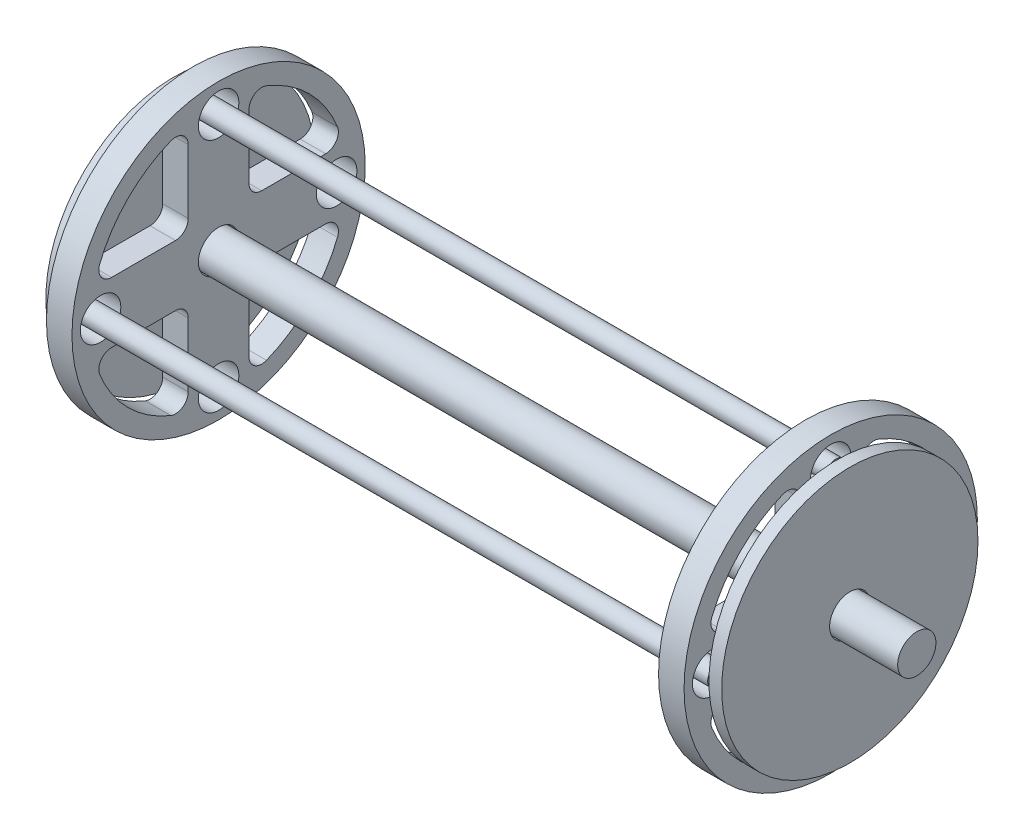
SolidWorks part; units mm, degrees
ref_plane "Front Plane" through (0, 0, 0) normal (0, 0, 1) x (1, 0, 0)
ref_plane "Top Plane" through (0, 0, 0) normal (0, 1, 0) x (1, 0, 0)
ref_plane "Right Plane" through (0, 0, 0) normal (1, 0, 0) x (0, 0, -1)
sketch "Sketch1" plane through (0, 0, 0) normal (1, 0, 0) x (0, 0, -1)
  circle A0 centre (0, 0) radius 3
  dimension "D1" = 6
extrude "Boss-Extrude1" add sketch "Sketch1" along normal mid plane 127
ref_plane "Plane1" through (46, 0, 0) normal (1, 0, 0) x (0, 0, -1)
sketch "Sketch2" plane through (46, 0, 0) normal (1, 0, 0) x (0, 0, -1)
  line L0 (0, 0) -> (0, 1.0694) construction
  line L1 (4.7625, 6.7625) -> (4.7625, 16.7892)
  line L2 (16.7892, 4.7625) -> (6.7625, 4.7625)
  line L3 (6.7625, -4.7625) -> (16.7892, -4.7625)
  line L4 (4.7625, -16.7892) -> (4.7625, -6.7625)
  line L5 (-4.7625, -6.7625) -> (-4.7625, -16.7892)
  line L6 (-16.7892, -4.7625) -> (-6.7625, -4.7625)
  line L7 (-6.7625, 4.7625) -> (-16.7892, 4.7625)
  line L8 (-4.7625, 16.7892) -> (-4.7625, 6.7625)
  circle A0 centre (0, 0) radius 3.175
  circle A1 centre (0, 18.5125) radius 1.5875 construction
  circle A2 centre (0, 18.5125) radius 3.175
  circle A3 centre (0, 0) radius 23
  circle A4 centre (-18.5125, 0) radius 1.5875 construction
  circle A5 centre (-18.5125, 0) radius 3.175
  circle A6 centre (0, -18.5125) radius 1.5875 construction
  circle A7 centre (0, -18.5125) radius 3.175
  circle A8 centre (18.5125, 0) radius 1.5875 construction
  circle A9 centre (18.5125, 0) radius 3.175
  circle A10 centre (0, 0) radius 20.1 construction
  circle A11 centre (0, 0) radius 18.5125 construction
  arc A13 (6.7625, -4.7625) -> (4.7625, -6.7625) centre (6.7625, -6.7625) ccw
  arc A15 (16.7892, -4.7625) -> (18.6444, -7.5097) centre (16.7892, -6.7625) cw
  arc A16 (4.7625, 6.7625) -> (6.7625, 4.7625) centre (6.7625, 6.7625) ccw
  arc A17 (7.5097, 18.6444) -> (18.6444, 7.5097) centre (0, 0) cw
  arc A18 (4.7625, 16.7892) -> (7.5097, 18.6444) centre (6.7625, 16.7892) cw
  arc A19 (16.7892, 4.7625) -> (18.6444, 7.5097) centre (16.7892, 6.7625) ccw
  arc A20 (18.6444, -7.5097) -> (7.5097, -18.6444) centre (0, 0) cw
  arc A21 (4.7625, -16.7892) -> (7.5097, -18.6444) centre (6.7625, -16.7892) ccw
  arc A22 (-4.7625, -6.7625) -> (-6.7625, -4.7625) centre (-6.7625, -6.7625) ccw
  arc A23 (-4.7625, -16.7892) -> (-7.5097, -18.6444) centre (-6.7625, -16.7892) cw
  arc A24 (-7.5097, -18.6444) -> (-18.6444, -7.5097) centre (0, 0) cw
  arc A25 (-16.7892, -4.7625) -> (-18.6444, -7.5097) centre (-16.7892, -6.7625) ccw
  arc A26 (-6.7625, 4.7625) -> (-4.7625, 6.7625) centre (-6.7625, 6.7625) ccw
  arc A27 (-16.7892, 4.7625) -> (-18.6444, 7.5097) centre (-16.7892, 6.7625) cw
  arc A28 (-18.6444, 7.5097) -> (-7.5097, 18.6444) centre (0, 0) cw
  arc A29 (-4.7625, 16.7892) -> (-7.5097, 18.6444) centre (-6.7625, 16.7892) ccw
  dimension "D2" = 3.175
  dimension "D3" = 6.35
  dimension "D4" = 46
  dimension "D5" = 40.2
  dimension "D6" = 37.025
  dimension "D7" = 4
  dimension "D8" = 2
  dimension "D9" = 2
  dimension "D10" = 2
extrude "Boss-Extrude2" add sketch "Sketch2" along normal blind 4 separate body
ref_plane "Plane2" through (51, 0, 0) normal (1, 0, 0) x (0, 0, -1)
sketch "Sketch3" plane through (51, 0, 0) normal (1, 0, 0) x (0, 0, -1)
  circle A1 centre (0, 0) radius 3.175
  circle A2 centre (0, 0) radius 20.1
  dimension "D1" = 6.35
extrude "Boss-Extrude3" add sketch "Sketch3" along normal blind 2 separate body
sketch "Sketch4" plane through (0, 0, 0) normal (1, 0, 0) x (0, 0, -1)
  circle A0 centre (0, 0) radius 20.1 construction
  circle A1 centre (0, 18.5125) radius 1.5875
  circle A2 centre (-18.5125, 0) radius 1.5875
  circle A3 centre (18.5125, 0) radius 1.5875
  circle A4 centre (0, -18.5125) radius 1.5875
  dimension "D1" = 40.2
  dimension "D2" = 4
extrude "Boss-Extrude4" add sketch "Sketch4" along normal mid plane 101.6 separate body
mirror "Mirror5" about plane through (0, 0, 0) normal (1, 0, 0) of bodies 103 102
